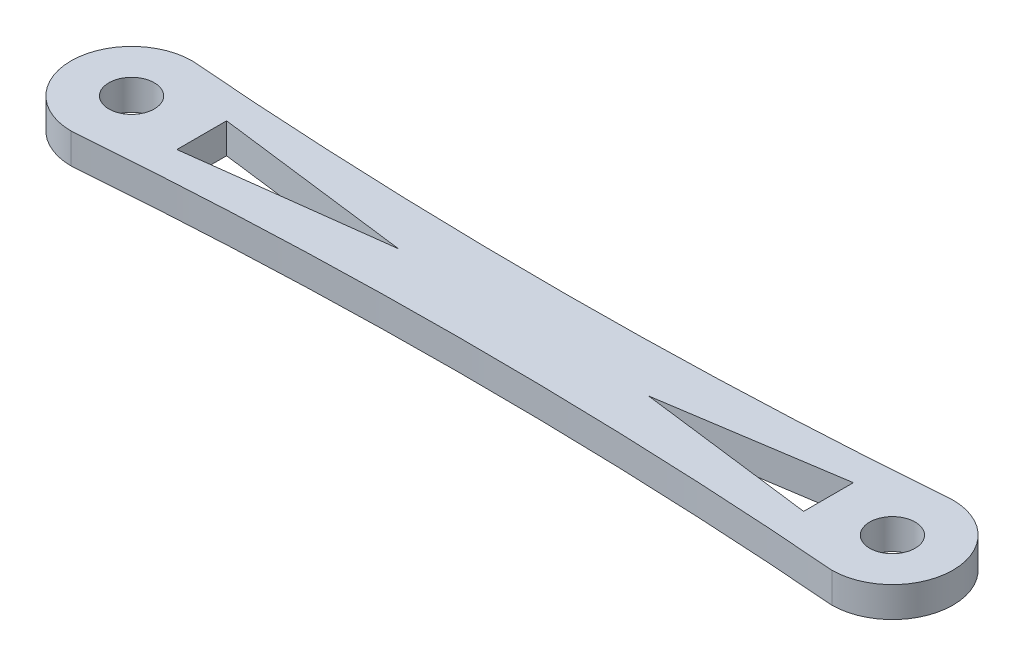
SolidWorks part; units mm, degrees
material "PF"
ref_plane "前视基准面" through (0, 0, 0) normal (0, 0, 1) x (1, 0, 0)
ref_plane "上视基准面" through (0, 0, 0) normal (0, 1, 0) x (1, 0, 0)
ref_plane "右视基准面" through (0, 0, 0) normal (1, 0, 0) x (0, 0, -1)
sketch "草图1" plane through (0, 0, 0) normal (0, 1, 0) x (1, 0, 0)
  arc A1 (0, 0) -> (0, -40) centre (0, -20) ccw
  arc A3 (251, 0) -> (251, -40) centre (251, -20) cw
  spline S0 degree 2 poles (0, 0) (125.5, -10) (251, 0) knots 0 0 0 1 1 1
  spline S1 degree 2 poles (0, -40) (125.5, -30) (251, -40) knots 0 0 0 1 1 1
  dimension "D1" = 251
  dimension "D2" = 40
extrude "凸台-拉伸1" add sketch "草图1" along normal blind 10
sketch "草图2" plane through (0, 10, 0) normal (0, 1, 0) x (1, 0, 0)
  circle A0 centre (0, -20) radius 7.5
  dimension "D1" = 15
extrude "切除-拉伸1" cut sketch "草图2" against normal through all
sketch "草图3" plane through (0, 10, 0) normal (0, 1, 0) x (1, 0, 0)
  circle A0 centre (251, -20) radius 7.5
  dimension "D1" = 15
extrude "切除-拉伸2" cut sketch "草图3" against normal through all
sketch "草图4" plane through (0, 10, 0) normal (0, 1, 0) x (1, 0, 0)
  line L0 (22.7999, -11.4559) -> (22.7999, -27.8606)
  line L1 (22.7999, -27.8606) -> (87.7351, -19.6582)
  line L2 (87.7351, -19.6582) -> (22.7999, -11.4559)
  line L3 (229.5671, -11.4559) -> (229.5671, -27.8606)
  line L4 (229.5671, -27.8606) -> (170.9846, -20.4607)
  line L5 (170.9846, -20.4607) -> (229.5671, -11.4559)
extrude "切除-拉伸3" cut sketch "草图4" against normal through all
